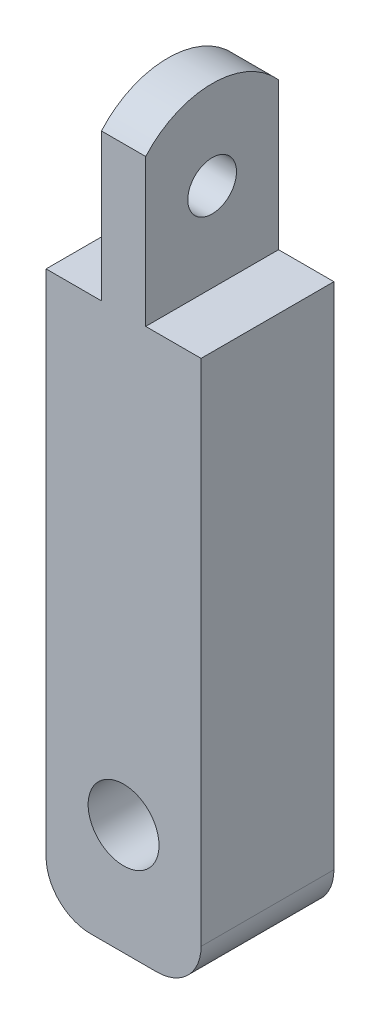
SolidWorks part; units mm, degrees
ref_plane "Front" through (0, 0, 0) normal (0, 0, 1) x (1, 0, 0)
ref_plane "Top" through (0, 0, 0) normal (0, 1, 0) x (1, 0, 0)
ref_plane "Right" through (0, 0, 0) normal (1, 0, 0) x (0, 0, -1)
sketch "Sketch1" plane through (0, 0, 0) normal (0, 0, 1) x (1, 0, 0)
  line L0 (-1, 12.5) -> (-1, 20.5)
  line L1 (-3.5, -12.5) -> (3.5, -12.5)
  line L2 (-3.5, -12.5) -> (-3.5, 12.5)
  line L3 (-3.5, 12.5) -> (-1, 12.5)
  line L4 (3.5, -12.5) -> (3.5, 12.5)
  line L5 (-3.5, -12.5) -> (3.5, 12.5) construction
  line L6 (-3.5, 12.5) -> (3.5, -12.5) construction
  line L7 (-1, 20.5) -> (1, 20.5)
  line L8 (1, 20.5) -> (1, 12.5)
  line L9 (0, 0) -> (0, 20.5) construction
  line L10 (1, 12.5) -> (3.5, 12.5)
  point P0 (0, 0)
  dimension "D1" = 7
  dimension "D2" = 25
  dimension "D3" = 8
  dimension "D4" = 2
extrude "Boss-Extrude1" add sketch "Sketch1" along normal blind 6
sketch "Sketch2" plane through (0, 0, 6) normal (0, 0, 1) x (1, 0, 0)
  line L0 (0, -12.5) -> (0, -7.5) construction
  line L1 (-3.5, -12.5) -> (3.5, -12.5) construction
  circle A0 centre (0, -7.5) radius 1.6
  dimension "D1" = 3.2
  dimension "D2" = 5
extrude "Cut-Extrude1" cut sketch "Sketch2" against normal through all
sketch "Sketch3" plane through (0, 0, 0) normal (0, 0, -1) x (-1, 0, 0)
  line L0 (0, -7.5) -> (0, -4.2957) construction
  line L1 (0, -4.2957) -> (-2.775, -5.8979)
  line L2 (-2.775, -5.8979) -> (-2.775, -9.1021)
  line L3 (-2.775, -9.1021) -> (0, -10.7043)
  line L4 (0, -10.7043) -> (2.775, -9.1021)
  line L5 (2.775, -9.1021) -> (2.775, -5.8979)
  line L6 (2.775, -5.8979) -> (0, -4.2957)
  circle A0 centre (0, -7.5) radius 2.775 construction
  dimension "D1" = 5.55
extrude "Cut-Extrude2" cut sketch "Sketch3" against normal blind 2.5
sketch "Sketch4" plane through (-1, 0, 0) normal (-1, 0, 0) x (0, 0, 1)
  line L0 (0, 20.5) -> (6, 12.5) construction
  circle A0 centre (3, 16.5) radius 1.1
  dimension "D1" = 2.2
extrude "Cut-Extrude3" cut sketch "Sketch4" against normal through all
sketch "Sketch5" plane through (-1, 0, 0) normal (-1, 0, 0) x (0, 0, 1)
  line L0 (0, 20.5) -> (0, 12.5) construction
  line L1 (6, 20.5) -> (6, 12.5) construction
  line L2 (6, 20.5) -> (0, 20.5) construction
  line L3 (0, 19.1458) -> (0, 20.5)
  line L4 (0, 20.5) -> (6, 20.5)
  line L5 (6, 20.5) -> (6, 19.1458)
  arc A0 (0, 19.1458) -> (6, 19.1458) centre (3, 16.5) cw
  line M2 (0, 20.5) -> (0, 12.5)
  line M4 (6, 12.5) -> (6, 20.5)
  line M5 (6, 20.5) -> (0, 20.5)
extrude "Cut-Extrude4" cut sketch "Sketch5" against normal through all contours A0 M5 M4 | A0 L4 M2
fillet "Fillet1" radius 2 2 edges at (3.5, -12.5, 3) (-3.5, -12.5, 3)
